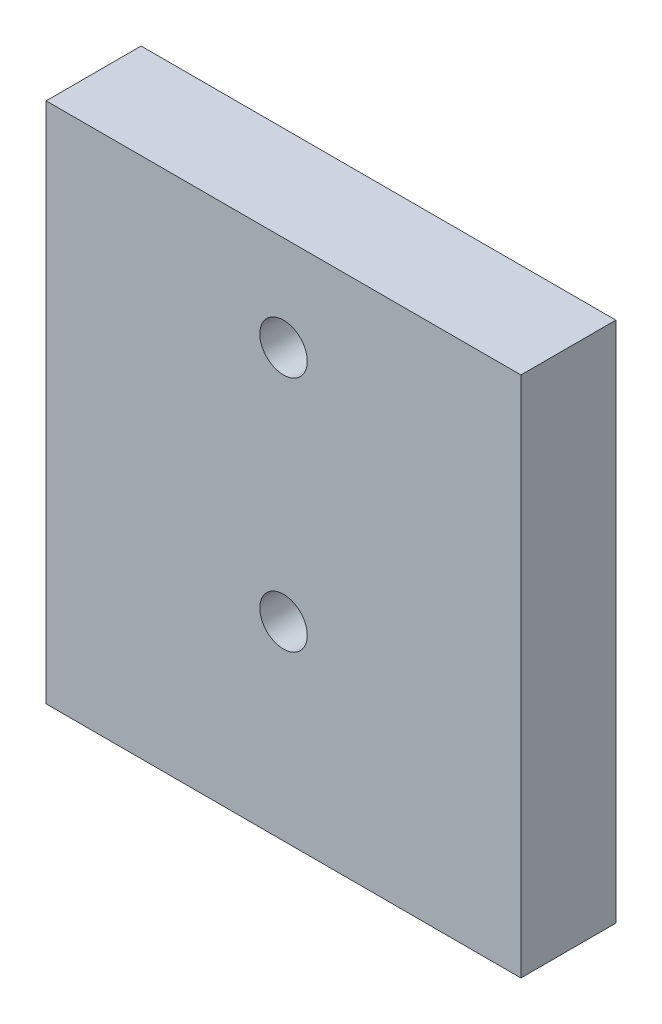
SolidWorks part; units mm, degrees
ref_plane "Спереди" through (0, 0, 0) normal (0, 0, 1) x (1, 0, 0)
ref_plane "Сверху" through (0, 0, 0) normal (0, 1, 0) x (1, 0, 0)
ref_plane "Справа" through (0, 0, 0) normal (1, 0, 0) x (0, 0, -1)
sketch "Эскиз1" plane through (0, 0, 0) normal (0, 0, 1) x (1, 0, 0)
  line L0 (-15, 21) -> (-15, -12)
  line L1 (-15, -12) -> (15, -12)
  line L2 (15, -12) -> (15, 21)
  line L3 (15, 21) -> (-15, 21)
  line L4 (0, 0) -> (0, 9568.4126) construction
  circle A0 centre (0, 0) radius 1.5
  circle A1 centre (0, 15) radius 1.5
  point P7 (0, 9.9227)
  dimension "D1" = 6
  dimension "D4" = 3
  dimension "D2" = 12
  dimension "D3" = 30
  dimension "D5" = 15
extrude "Бобышка-Вытянуть1" add sketch "Эскиз1" along normal blind 6
